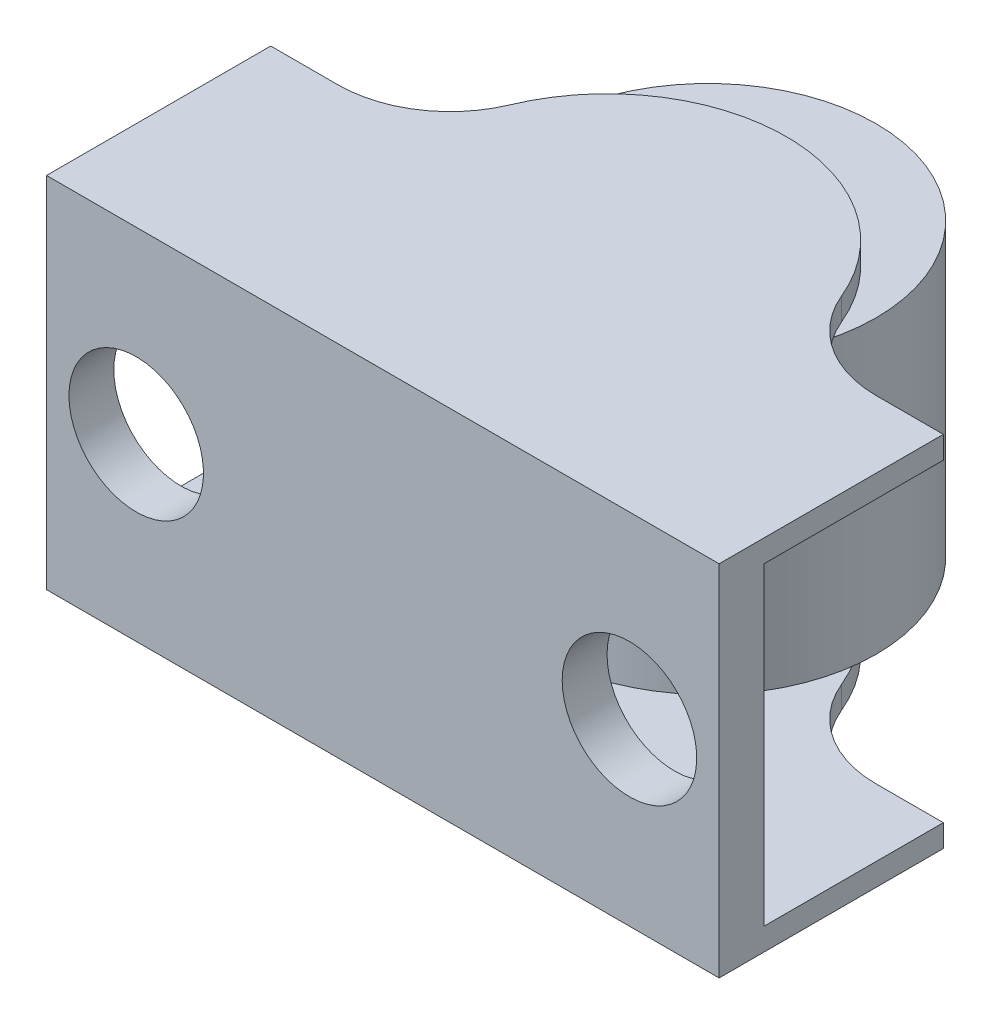
SolidWorks part; units mm, degrees
ref_plane "前基準面" through (0, 0, 0) normal (0, 0, 1) x (1, 0, 0)
ref_plane "上基準面" through (0, 0, 0) normal (0, 1, 0) x (1, 0, 0)
ref_plane "右基準面" through (0, 0, 0) normal (1, 0, 0) x (0, 0, -1)
sketch "草圖1" plane through (0, 0, 0) normal (0, 0, 1) x (1, 0, 0)
  line L1 (-15, 8) -> (15, 8)
  line L2 (-15, 8) -> (-15, -8)
  line L3 (-15, -8) -> (15, -8)
  line L4 (15, 8) -> (15, -8)
  line L5 (0, -8) -> (0, 8) construction
  line L6 (-15, 0) -> (15, 0) construction
  point P0 (0, 0)
  dimension "D1" = 30
  dimension "D2" = 16
extrude "填料-伸長1" add sketch "草圖1" along normal blind 2
sketch "草圖2" plane through (0, 8, 0) normal (0, 1, 0) x (1, 0, 0)
  line L0 (-15, 0) -> (15, 0)
  line L1 (15, 0) -> (15, 8)
  line L2 (15, 8) -> (12, 8)
  line L3 (-15, 0) -> (-15, 8)
  line L4 (-15, 8) -> (-12, 8)
  line L5 (0, -7.2332) -> (0, 3.9544) construction
  line L6 (15, -2) -> (-15, -2) construction
  arc A0 (7.3846, 11.0769) -> (-7.3846, 11.0769) centre (0, 8) ccw
  arc A1 (12, 8) -> (7.3846, 11.0769) centre (12, 13) cw
  arc A2 (-12, 8) -> (-7.3846, 11.0769) centre (-12, 13) ccw
  point P16 (12, 1.8015)
  point P17 (0, 16)
  point P20 (-15, 8)
  point P21 (0, 3.9544)
  point P22 (-12, 8)
  dimension "D1" = 8
  dimension "D2" = 5
  dimension "D3" = 18
  dimension "D4" = 8
extrude "填料-伸長2" add sketch "草圖2" against normal blind 1
mirror "鏡射1" about plane through (0, 0, 0) normal (0, 1, 0) of "填料-伸長2"
sketch "草圖3" plane through (0, 8, 0) normal (0, 1, 0) x (1, 0, 0)
  circle A0 centre (0, 12) radius 2.5
  arc A1 (7.3846, 11.0769) -> (-7.3846, 11.0769) centre (0, 8) ccw construction
  arc A2 (7.3846, 11.0769) -> (-7.3846, 11.0769) centre (0, 8) ccw construction
  point P3 (0, 14.5)
  point P6 (0, 16)
  dimension "D1" = 1.5
  dimension "D2" = 5
extrude "填料-伸長3" add sketch "草圖3" against normal up to surface (15 mm away) up to face at (0, -7, -7.2099)
ref_plane "平面1" through (0, 0, -12.5) normal (0, 0, -1) x (-1, 0, 0)
sketch "草圖4" plane through (0, 0, -12.5) normal (0, 0, -1) x (-1, 0, 0)
  line L6 (0, 6.5) -> (7.5, 6.5)
  line L7 (0, 6.5) -> (0, -6.5)
  line L8 (0, -6.5) -> (7.5, -6.5)
  line L9 (7.5, 6.5) -> (7.5, -6.5)
  point P4 (0, 0)
  dimension "D2" = 13
  dimension "D1" = 7.5
revolve "旋轉1" add sketch "草圖4" angle 360 about L7
sketch "草圖5" plane through (0, 0, 0) normal (0, 0, -1) x (-1, 0, 0)
  line L0 (-17.8926, 0) -> (17.8926, 0) construction
  line L1 (0, -11.0167) -> (0, 10.2849) construction
  circle A0 centre (-11, 0) radius 3
  circle A1 centre (11, 0) radius 3
  dimension "D1" = 11
  dimension "D2" = 6
extrude "除料-伸長1" cut sketch "草圖5" against normal through all
